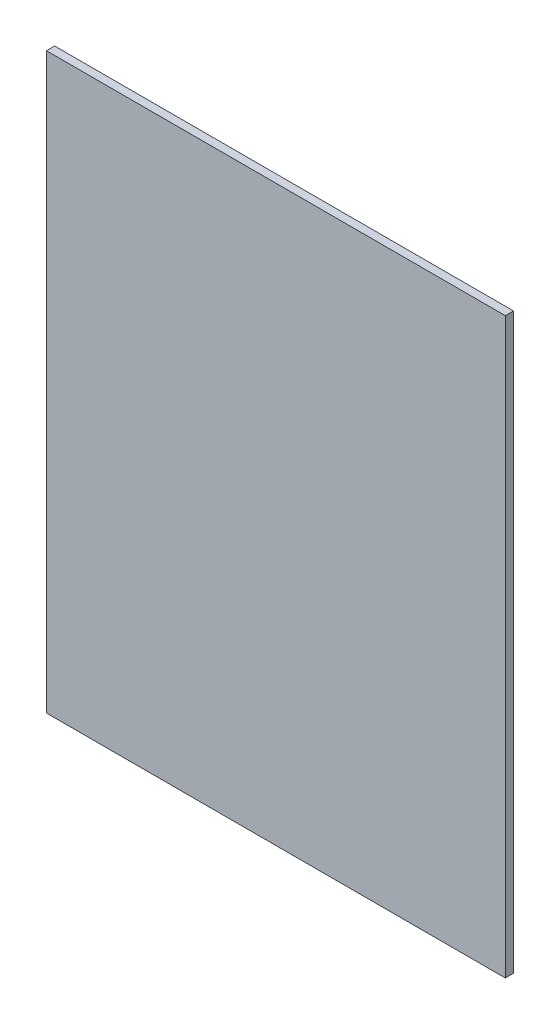
SolidWorks part; units mm, degrees
ref_plane "前视基准面" through (0, 0, 0) normal (0, 0, 1) x (1, 0, 0)
ref_plane "上视基准面" through (0, 0, 0) normal (0, 1, 0) x (1, 0, 0)
ref_plane "右视基准面" through (0, 0, 0) normal (1, 0, 0) x (0, 0, -1)
sketch "草图1" plane through (0, 0, 0) normal (0, 0, 1) x (1, 0, 0)
  line L1 (0, 0) -> (560, 0)
  line L2 (0, 0) -> (0, -700)
  line L3 (0, -700) -> (560, -700)
  line L4 (560, 0) -> (560, -700)
extrude "凸台-拉伸1" add sketch "草图1" along normal blind 10
